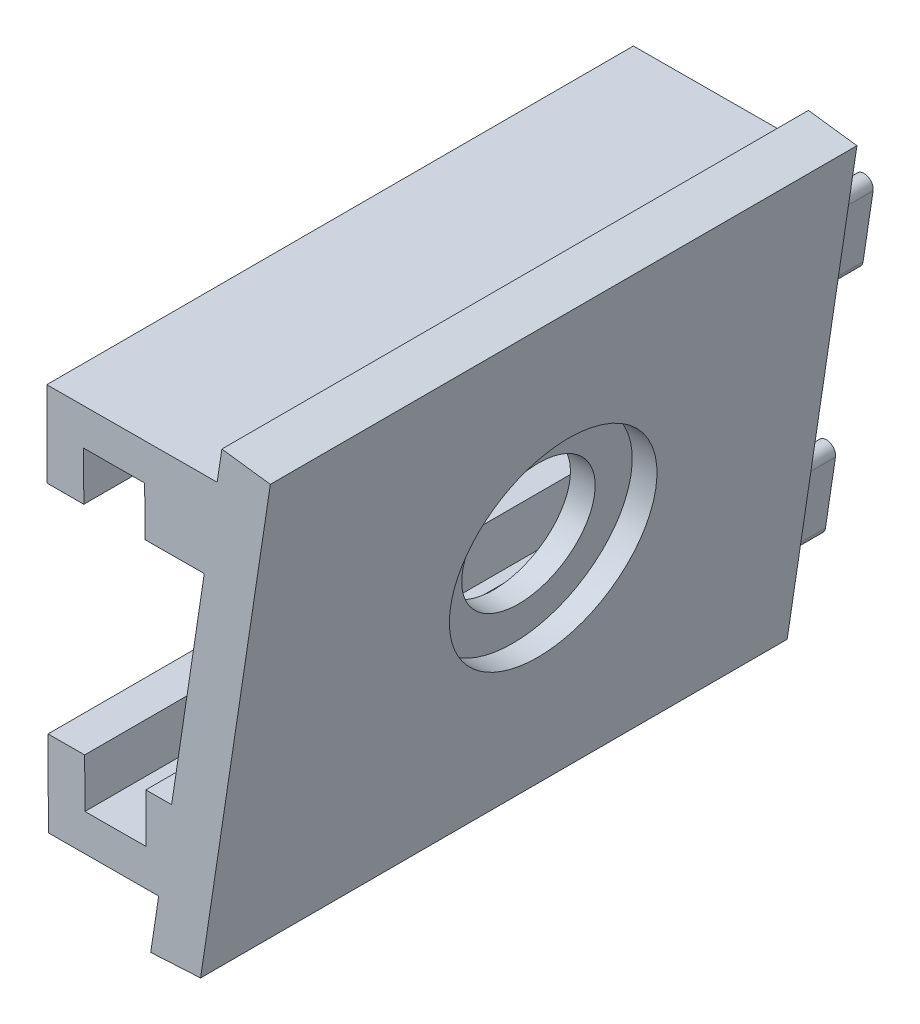
SolidWorks part; units mm, degrees
ref_plane "Front Plane" through (0, 0, 0) normal (0, 0, 1) x (1, 0, 0)
ref_plane "Top Plane" through (0, 0, 0) normal (0, 1, 0) x (1, 0, 0)
ref_plane "Right Plane" through (0, 0, 0) normal (1, 0, 0) x (0, 0, -1)
sketch "Sketch1" plane through (0, 0, 0) normal (0, 0, 1) x (1, 0, 0)
  line L8 (-336.0521, 10.5982) -> (-334.0685, 10.3393) construction
  line L9 (-336.0521, 10.5982) -> (-338.9626, -8.6942) construction
  line L10 (-334.0685, 10.3393) -> (-336.9228, -8.5804) construction
  line L11 (-336.9228, -8.5804) -> (-338.9626, -8.6942) construction
  line L12 (-336.0521, 10.5982) -> (-336.244, 9.3264)
  line L13 (-338.9626, -8.6942) -> (-336.9228, -8.5804)
  line L14 (-336.9228, -8.5804) -> (-334.0685, 10.3393)
  line L15 (-334.0685, 10.3393) -> (-336.0521, 10.5982)
  line L81 (-341.7007, 5.8143) -> (-343.2008, 5.8143)
  line L82 (-343.2008, 5.8143) -> (-343.215, 9.2979)
  line L83 (-343.215, 9.2979) -> (-336.244, 9.3264)
  line L85 (-341.7089, 7.804) -> (-341.6997, 5.554)
  line L86 (-339.2089, 7.8143) -> (-341.7089, 7.804)
  line L87 (-339.2007, 5.8143) -> (-339.2089, 7.8143)
  line L88 (-336.8111, 5.8241) -> (-339.2007, 5.8143)
  line L89 (-341.7089, 7.804) -> (-341.7007, 5.8143) construction
  line L90 (-339.2089, 7.8143) -> (-341.7089, 7.804) construction
  line L91 (-339.2007, 5.8143) -> (-339.2089, 7.8143) construction
  line L92 (-336.7723, 5.8242) -> (-339.2007, 5.8143)
  line L95 (-338.9626, -8.6942) -> (-336.0521, 10.5982) construction
  line L97 (-336.7723, 5.8242) -> (-338.1083, -3.0313)
  line L103 (-341.6644, -3.0459) -> (-343.1644, -3.052)
  line L104 (-343.1644, -3.052) -> (-343.1501, -6.552)
  line L105 (-343.1501, -6.552) -> (-338.6366, -6.5335)
  line L107 (-341.6562, -5.0459) -> (-341.6654, -2.7959)
  line L108 (-339.1562, -5.0356) -> (-341.6562, -5.0459)
  line L109 (-339.1644, -3.0356) -> (-339.1562, -5.0356)
  line L110 (-338.0695, -3.0312) -> (-339.1644, -3.0356)
  line L111 (-341.6562, -5.0459) -> (-341.6644, -3.0459) construction
  line L112 (-339.1562, -5.0356) -> (-341.6562, -5.0459) construction
  line L113 (-339.1644, -3.0356) -> (-339.1562, -5.0356) construction
  line L114 (-338.1083, -3.0313) -> (-339.1644, -3.0356)
  line L115 (-341.4154, -2.7949) -> (-351.2008, -2.835) construction
  line L116 (-338.6366, -6.5335) -> (-338.9626, -8.6942)
  line L117 (-341.7007, 5.8143) -> (-339.2007, 5.8143)
  line L118 (-341.6644, -3.0459) -> (-339.1644, -3.0356)
  dimension "D3" = 1.5
  dimension "D4" = 1.5
  dimension "D6" = 0.25
  dimension "D7" = 1.5
  dimension "D8" = 1.5
  dimension "D2" = 0.25
  dimension "D5" = 0.25
extrude "Boss-Extrude1" add sketch "Sketch1" against normal up to surface (24 mm away) contours L105 L116 L13 L14 L15 L12 L83 L82 L81 L89 L90 L91 L92 L97 L114 L113 L112 L111 L103 L104 | L89 L117 L91 L90 | L118 L111 L112 L113
sketch "Sketch2" plane through (0, 0, 0) normal (0, 0, -1) x (-1, 0, 0)
  line L0 (335.0603, 10.4687) -> (337.9427, -8.6373) construction
  line L3 (335.5266, 7.3781) -> (335.9368, 4.6589) construction
  line L4 (335.8974, 7.434) -> (336.3076, 4.7148)
  line L5 (335.1558, 7.3222) -> (335.566, 4.6029)
  line L6 (337.0663, -2.828) -> (337.4765, -5.5473) construction
  line L7 (337.4371, -2.7721) -> (337.8473, -5.4913)
  line L8 (336.6955, -2.884) -> (337.1057, -5.6032)
  line L10 (334.0685, 10.3393) -> (336.0521, 10.5982) construction
  line L11 (338.9626, -8.6942) -> (336.9228, -8.5804) construction
  arc A0 (335.8974, 7.434) -> (335.1558, 7.3222) centre (335.5266, 7.3781) ccw
  arc A1 (335.566, 4.6029) -> (336.3076, 4.7148) centre (335.9368, 4.6589) ccw
  arc A2 (337.4371, -2.7721) -> (336.6955, -2.884) centre (337.0663, -2.828) ccw
  arc A3 (337.1057, -5.6032) -> (337.8473, -5.4913) centre (337.4765, -5.5473) ccw
  point P8 (335.7317, 6.0185)
  point P15 (337.2714, -4.1876)
  dimension "D1" = 0.75
  dimension "D2" = 2.75
  dimension "D5" = 2.75
  dimension "D6" = 3.125
  dimension "D4" = 0.75
  dimension "D3" = 3.125
extrude "Boss-Extrude2" add sketch "Sketch2" along normal blind 1.75
sketch "Sketch3" plane through (0, 0, 24) normal (0, 0, 1) x (1, 0, 0)
  line L0 (-339.1562, -5.0356) -> (-341.6562, -5.0459) construction
  line L1 (-341.6562, -5.0459) -> (-341.6644, -3.0459) construction
  line L2 (-341.6644, -3.0459) -> (-339.1644, -3.0356) construction
  line L3 (-339.1644, -3.0356) -> (-339.1562, -5.0356) construction
  line L4 (-341.7089, 7.804) -> (-341.7007, 5.8143) construction
  line L5 (-339.2089, 7.8143) -> (-341.7089, 7.804) construction
  line L6 (-341.7007, 5.8143) -> (-339.2007, 5.8143) construction
  line L7 (-339.2007, 5.8143) -> (-339.2089, 7.8143) construction
  line L8 (-339.1562, -5.0356) -> (-341.6562, -5.0459)
  line L9 (-341.6562, -5.0459) -> (-341.6644, -3.0459)
  line L10 (-341.6644, -3.0459) -> (-339.1644, -3.0356)
  line L11 (-339.1644, -3.0356) -> (-339.1562, -5.0356)
  line L12 (-341.7089, 7.804) -> (-341.7007, 5.8143)
  line L13 (-339.2089, 7.8143) -> (-341.7089, 7.804)
  line L14 (-341.7007, 5.8143) -> (-339.2007, 5.8143)
  line L15 (-339.2007, 5.8143) -> (-339.2089, 7.8143)
extrude "Cut-Extrude1" cut sketch "Sketch3" against normal up to vertex (22 mm away)
ref_plane "Plane1" through (-334.0205, -1.3693, 0) normal (-1, -0.0041, 0) x (0, 0, -1)
sketch "Sketch6" plane through (-334.0205, -1.3693, 0) normal (-1, -0.0041, 0) x (0, 0, -1)
  circle A0 centre (-11, -2.2548) radius 2.7 construction
  circle A1 centre (-11, -2.2548) radius 2.7
extrude "Cut-Extrude2" cut sketch "Sketch6" along normal through all
sketch "Sketch7" plane through (-334.0205, -1.3693, 0) normal (-1, -0.0041, 0) x (0, 0, -1)
  circle A3 centre (-11, -2.2548) radius 4.2
  circle A4 centre (-11, -2.2548) radius 2.7 construction
  dimension "D1" = 1.5
extrude "Cut-Extrude3" cut sketch "Sketch7" along normal offset from surface (3.1291 mm away) 1
equation "\"D6@Sketch2\"=\"D3@Sketch2\""
equation "\"D4@Sketch1\"=\"D3@Sketch1\""
equation "\"D8@Sketch1\"=\"D7@Sketch1\""
